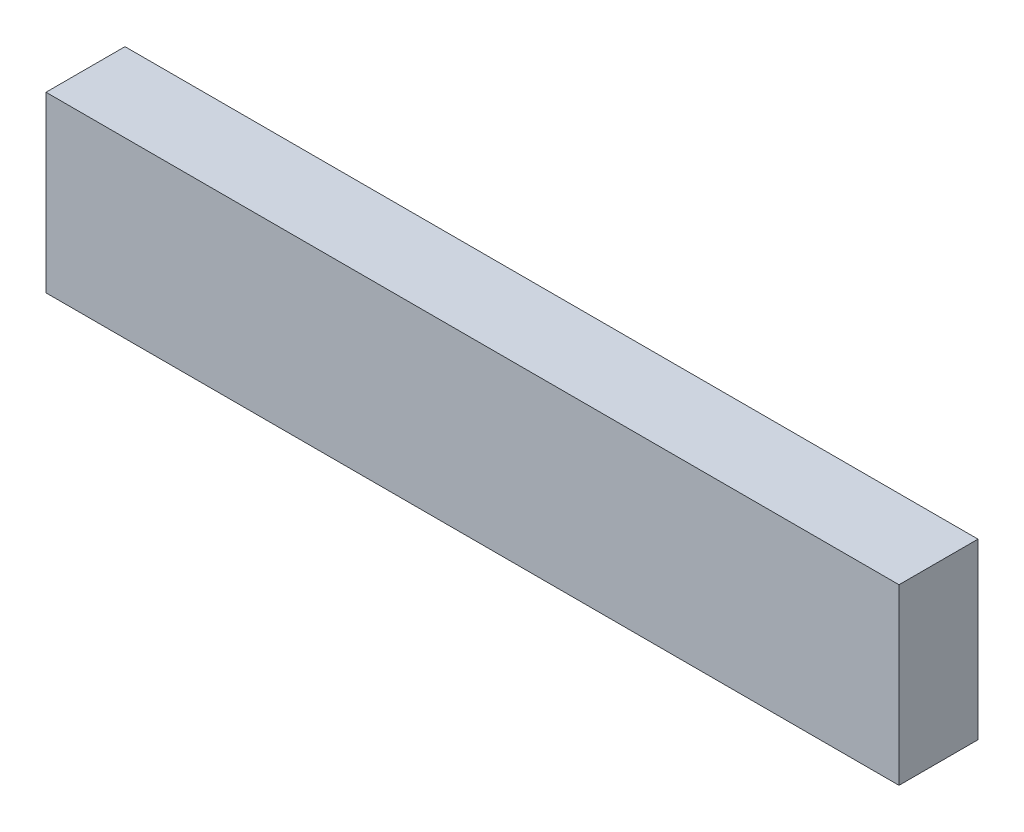
SolidWorks part; units mm, degrees
ref_plane "前视基准面" through (0, 0, 0) normal (0, 0, 1) x (1, 0, 0)
ref_plane "上视基准面" through (0, 0, 0) normal (0, 1, 0) x (1, 0, 0)
ref_plane "右视基准面" through (0, 0, 0) normal (1, 0, 0) x (0, 0, -1)
sketch "草图1" plane through (0, 0, 0) normal (0, 0, 1) x (1, 0, 0)
  line L1 (-52.6918, 25.9722) -> (217.3082, 25.9722)
  line L2 (-52.6918, 25.9722) -> (-52.6918, -29.0278)
  line L3 (-52.6918, -29.0278) -> (217.3082, -29.0278)
  line L4 (217.3082, 25.9722) -> (217.3082, -29.0278)
  dimension "D1" = 270
  dimension "D2" = 55
extrude "凸台-拉伸1" add sketch "草图1" along normal blind 25
